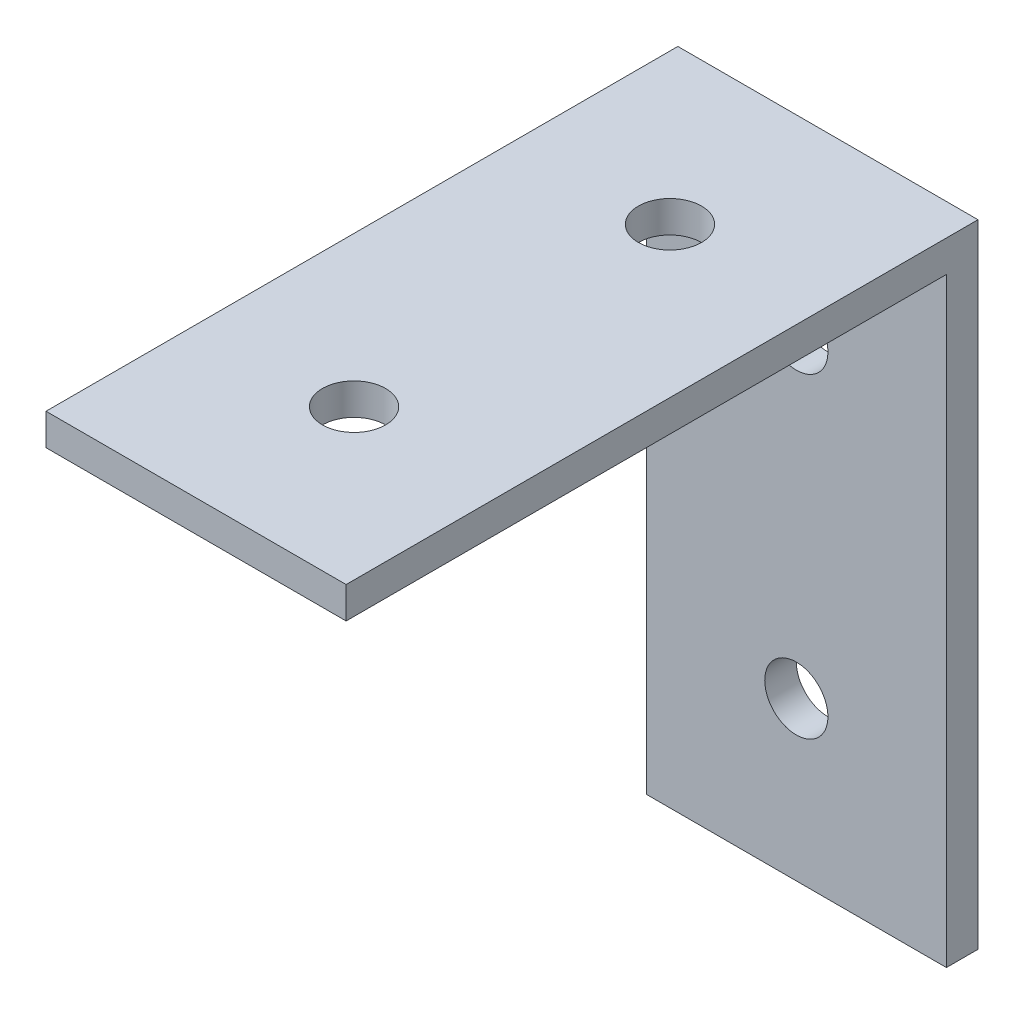
SolidWorks part; units mm, degrees
ref_plane "Front Plane" through (0, 0, 0) normal (0, 0, 1) x (1, 0, 0)
ref_plane "Top Plane" through (0, 0, 0) normal (0, 1, 0) x (1, 0, 0)
ref_plane "Right Plane" through (0, 0, 0) normal (1, 0, 0) x (0, 0, -1)
sketch "Sketch1" plane through (0, 0, 0) normal (0, 0, 1) x (1, 0, 0)
  line L1 (-9.5, -20) -> (9.5, -20)
  line L2 (-9.5, -20) -> (-9.5, 20)
  line L3 (-9.5, 20) -> (9.5, 20)
  line L4 (9.5, -20) -> (9.5, 20)
  line L5 (-9.5, -20) -> (9.5, 20) construction
  line L6 (-9.5, 20) -> (9.5, -20) construction
  point P0 (0, 0)
  dimension "D1" = 19
  dimension "D2" = 40
extrude "Boss-Extrude1" add sketch "Sketch1" along normal blind 2
sketch "Sketch2" plane through (0, 0, 2) normal (0, 0, 1) x (1, 0, 0)
  line L0 (9.5, -20) -> (9.5, 20) construction
  line L1 (-9.5, 20) -> (9.5, 20)
  line L2 (-9.5, 20) -> (-9.5, 18)
  line L3 (-9.5, 18) -> (9.5, 18)
  line L4 (9.5, 20) -> (9.5, 18)
  dimension "D1" = 2
extrude "Boss-Extrude2" add sketch "Sketch2" along normal blind 38
sketch "Sketch3" plane through (0, 0, 0) normal (0, 0, -1) x (-1, 0, 0)
  line L0 (0, 20) -> (0, -20) construction
  line L1 (-9.5, 20) -> (9.5, 20) construction
  line L2 (9.5, -20) -> (-9.5, -20) construction
  circle A0 centre (0, 10) radius 2
  circle A1 centre (0, -10) radius 2
  dimension "D1" = 4
  dimension "D2" = 4
  dimension "D3" = 10
  dimension "D4" = 10
extrude "Cut-Extrude1" cut sketch "Sketch3" against normal blind 10
sketch "Sketch4" plane through (0, 20, 0) normal (0, 1, 0) x (1, 0, 0)
  line L0 (0, 0) -> (0, -40) construction
  line L1 (9.5, -40) -> (-9.5, -40) construction
  line L2 (9.5, 0) -> (-9.5, 0) construction
  circle A0 centre (0, -10) radius 2
  circle A1 centre (0, -30) radius 2
  dimension "D1" = 4
  dimension "D2" = 4
  dimension "D4" = 10
  dimension "D3" = 10
extrude "Cut-Extrude2" cut sketch "Sketch4" against normal blind 10
